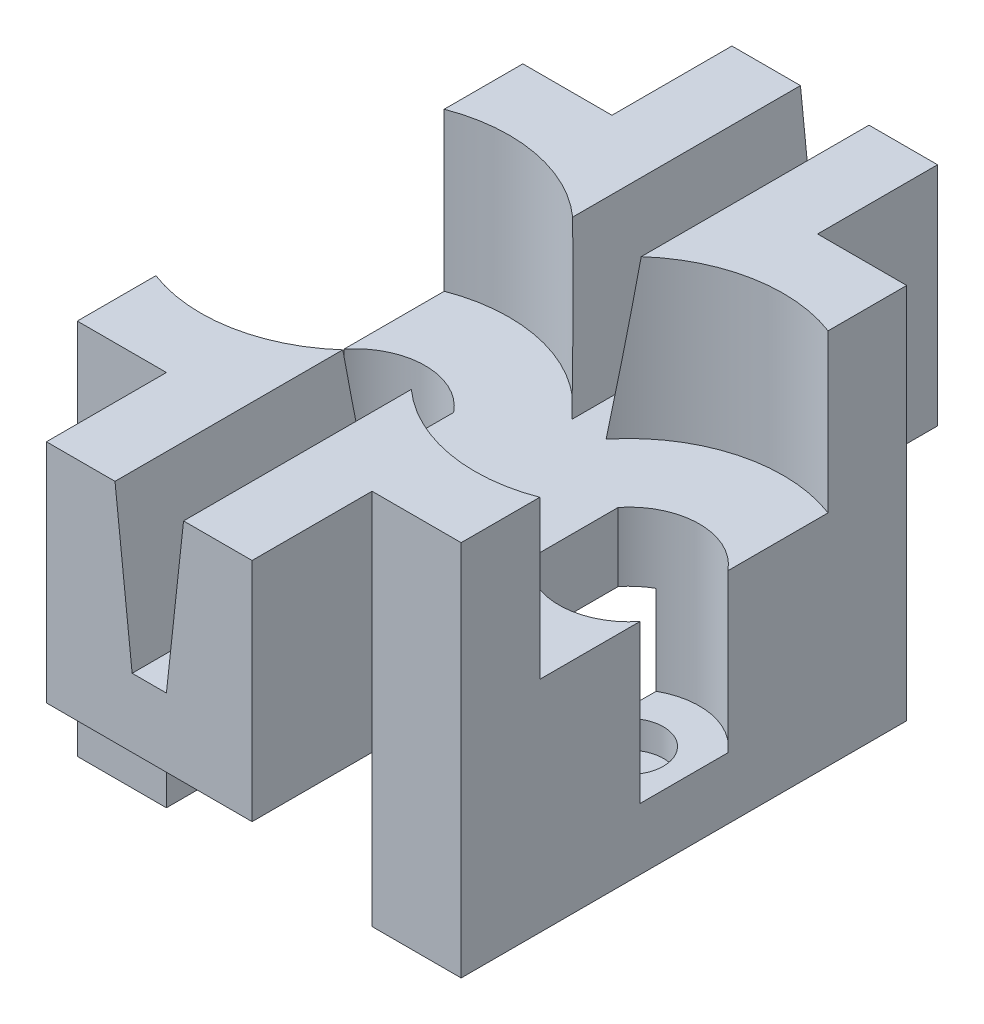
SolidWorks part; units mm, degrees
ref_plane "Front Plane" through (0, 0, 0) normal (0, 0, 1) x (1, 0, 0)
ref_plane "Top Plane" through (0, 0, 0) normal (0, 1, 0) x (1, 0, 0)
ref_plane "Right Plane" through (0, 0, 0) normal (1, 0, 0) x (0, 0, -1)
sketch "Sketch1" plane through (0, 0, 0) normal (0, 1, 0) x (1, 0, 0)
  line L1 (-28, -50) -> (28, -50)
  line L2 (-28, -50) -> (-28, 50)
  line L3 (-28, 50) -> (28, 50)
  line L4 (28, -50) -> (28, 50)
  line L5 (-28, -50) -> (28, 50) construction
  line L6 (-28, 50) -> (28, -50) construction
  point P0 (0, 0)
  dimension "D1" = 100
  dimension "D2" = 56
extrude "Boss-Extrude1" add sketch "Sketch1" along normal blind 55
sketch "Sketch3" plane through (0, 0, 50) normal (0, 0, 1) x (1, 0, 0)
  line L0 (2.5, 55) -> (2.5, 32) construction
  line L1 (-28, 55) -> (28, 55) construction
  line L3 (-28, 55) -> (-28, 0) construction
  line L4 (-2.5, 32) -> (-2.5, 55) construction
  line L5 (28, 55) -> (28, 0) construction
  line L11 (-2.5, 32) -> (-5, 55)
  line L13 (5, 55) -> (2.5, 32)
  line L14 (-2.5, 32) -> (2.5, 32)
  line L15 (-5, 55) -> (5, 55)
  dimension "D1" = 23
  dimension "D2" = 30.5
  dimension "D3" = 23
  dimension "D4" = 30.5
  dimension "D5" = 10
  dimension "D6" = 2.5
extrude "Cut-Extrude2" cut sketch "Sketch3" against normal through all
sketch "Sketch7" plane through (0, 55, 0) normal (0, 1, 0) x (1, 0, 0)
  line L0 (-2.5, 50) -> (-2.5, -50) construction
  line L3 (28, 50) -> (5, 50) construction
  circle A0 centre (20, 0) radius 10
  circle A1 centre (20, 0) radius 21.5 construction
  circle A2 centre (20, 0) radius 22.5
  dimension "D1" = 20
  dimension "D3" = 43
  dimension "D4" = 1
  dimension "D5" = 50
  dimension "D2" = 22.5
extrude "Cut-Extrude4" cut sketch "Sketch7" against normal blind 23
sketch "Sketch9" plane through (0, 55, 0) normal (0, 1, 0) x (1, 0, 0)
  line L0 (12, 6.408) -> (12, -6.408)
  circle A0 centre (20, 0) radius 10.25 construction
  arc A1 (12, 6.408) -> (12, -6.408) centre (20, 0) cw
  circle A2 centre (20, 0) radius 22.5 construction
  dimension "D1" = 20.5
  dimension "D2" = 8
extrude "Cut-Extrude5" cut sketch "Sketch9" against normal blind 46
sketch "Sketch10" plane through (0, 9, 0) normal (0, 1, 0) x (1, 0, 0)
  line L0 (16, 3) -> (16, -3)
  arc A1 (16, 3) -> (16, -3) centre (20, 0) cw
  arc A2 (28, 6.408) -> (12, 6.408) centre (20, 0) ccw construction
  dimension "D1" = 6
  dimension "D2" = 5
  dimension "D3" = 0
  dimension "D4" = 0
extrude "Cut-Extrude6" cut sketch "Sketch10" against normal blind 4
sketch "Sketch11" plane through (0, 55, 0) normal (0, 1, 0) x (1, 0, 0)
  line L0 (12, 6.408) -> (12, -6.408)
  arc A0 (12, 6.408) -> (12, -6.408) centre (19.6771, 0) ccw
extrude "Cut-Extrude7" cut sketch "Sketch11" against normal blind 23
mirror "Mirror1" about plane through (0, 0, 0) normal (1, 0, 0) of "Cut-Extrude7", "Cut-Extrude4", "Cut-Extrude5", "Cut-Extrude6"
sketch "Sketch12" plane through (0, 55, 0) normal (0, 1, 0) x (1, 0, 0)
  line L0 (-5, 50) -> (-5, 16.7705) construction
  line L1 (-28, 50) -> (-15, 50)
  line L2 (-28, 50) -> (-28, 32.5)
  line L3 (-28, 32.5) -> (-15, 32.5)
  line L4 (-15, 50) -> (-15, 32.5)
  line L5 (28, 50) -> (15, 50)
  line L6 (28, 50) -> (28, 32.5)
  line L7 (28, 32.5) -> (15, 32.5)
  line L8 (15, 50) -> (15, 32.5)
  line L9 (-28, -50) -> (-15, -50)
  line L10 (-28, -50) -> (-28, -32.5)
  line L11 (-28, -32.5) -> (-15, -32.5)
  line L12 (-15, -50) -> (-15, -32.5)
  line L13 (28, -50) -> (15, -50)
  line L14 (28, -50) -> (28, -32.5)
  line L15 (28, -32.5) -> (15, -32.5)
  line L16 (15, -50) -> (15, -32.5)
  line L17 (5, 50) -> (5, 16.7705) construction
  line L18 (5, -16.7705) -> (5, -50) construction
  line L19 (-5, -16.7705) -> (-5, -50) construction
  arc A1 (-28, -21.0297) -> (-5, -16.7705) centre (-20, 0) ccw construction
  arc A2 (2.5, -14.1421) -> (28, -21.0297) centre (20, 0) ccw construction
  arc A3 (28, 21.0297) -> (5, 16.7705) centre (20, 0) ccw construction
  arc A4 (-5, 16.7705) -> (-28, 21.0297) centre (-20, 0) ccw construction
  dimension "D5" = 32.5
  dimension "D1" = 10
  dimension "D2" = 10
  dimension "D3" = 10
  dimension "D4" = 10
  dimension "D6" = 32.5
  dimension "D7" = 32.5
  dimension "D8" = 32.5
extrude "Cut-Extrude8" cut sketch "Sketch12" against normal through all
sketch "Sketch13" plane through (0, 0, 50) normal (0, 0, 1) x (1, 0, 0)
  line L0 (15, 0) -> (15, 55) construction
  line L1 (-15, 0) -> (15, 0)
  line L2 (-15, 0) -> (-15, 22)
  line L3 (-15, 22) -> (15, 22)
  line L4 (15, 0) -> (15, 22)
  dimension "D1" = 22
extrude "Cut-Extrude9" cut sketch "Sketch13" against normal through all
